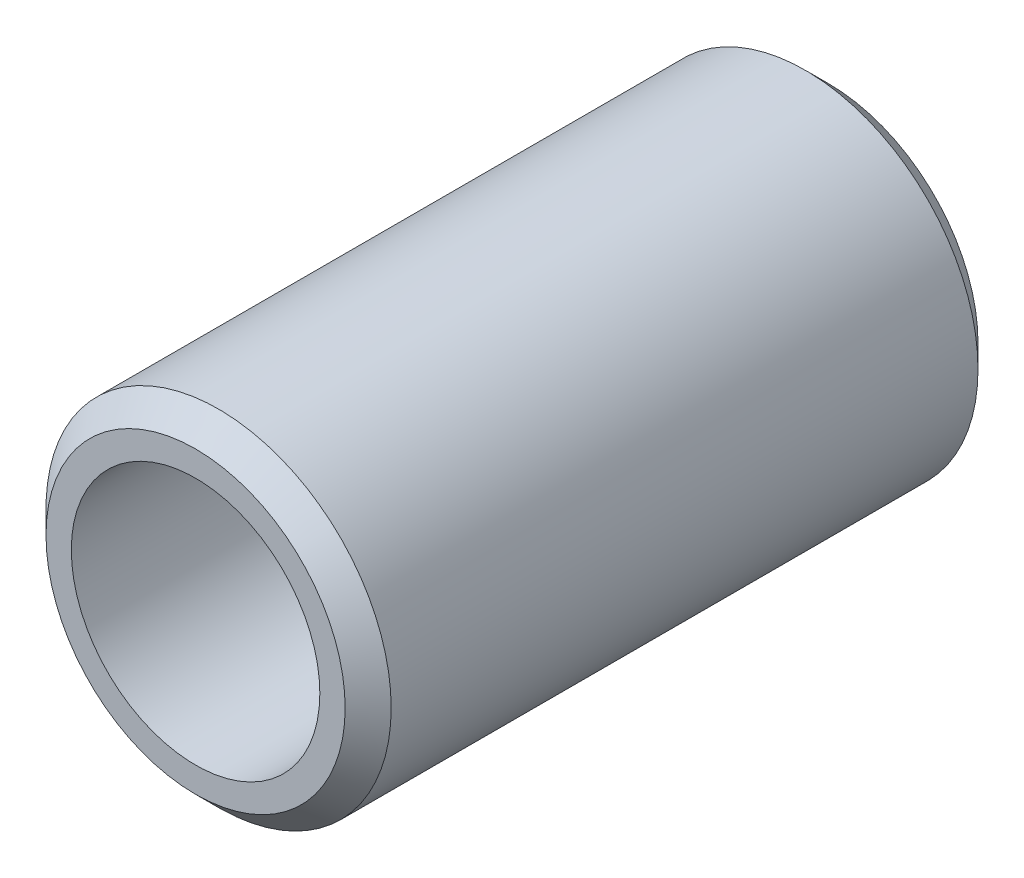
SolidWorks part; units mm, degrees
ref_plane "Front Plane" through (0, 0, 0) normal (0, 0, 1) x (1, 0, 0)
ref_plane "Top Plane" through (0, 0, 0) normal (0, 1, 0) x (1, 0, 0)
ref_plane "Right Plane" through (0, 0, 0) normal (1, 0, 0) x (0, 0, -1)
sketch "Sketch1" plane through (0, 0, 0) normal (0, 0, 1) x (1, 0, 0)
  circle A0 centre (0, 0) radius 6.858
  circle A1 centre (0, 0) radius 9.525
  dimension "D1" = 19.05
  dimension "D2" = 13.716
extrude "Boss-Extrude1" add sketch "Sketch1" along normal mid plane 34.925
chamfer "Chamfer1" distance 1.27 angle 45 2 edges at (9.525, 0, 17.4625) (9.525, 0, -17.4625)
